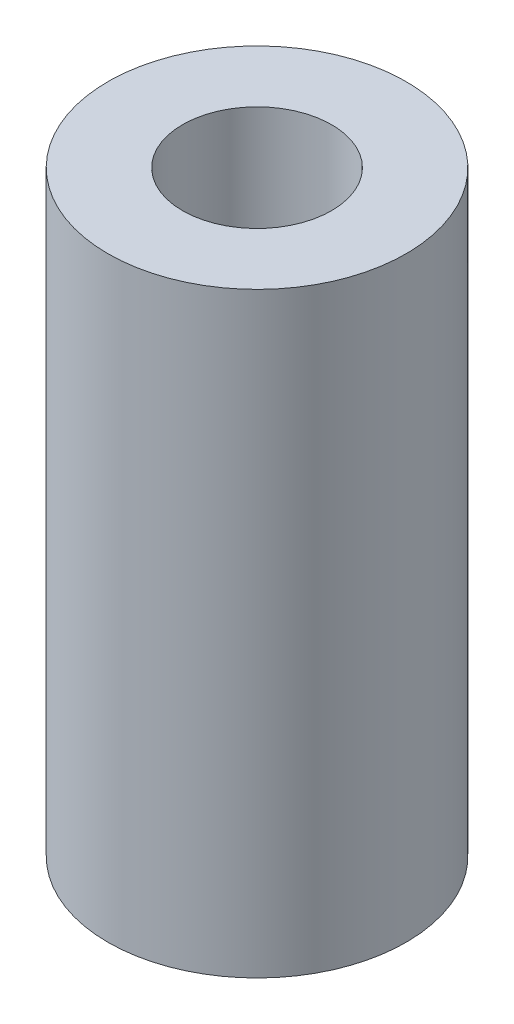
SolidWorks part; units mm, degrees
material "6061-T6 (SS)"
ref_plane "Front Plane" through (0, 0, 0) normal (0, 0, 1) x (1, 0, 0)
ref_plane "Top Plane" through (0, 0, 0) normal (0, 1, 0) x (1, 0, 0)
ref_plane "Right Plane" through (0, 0, 0) normal (1, 0, 0) x (0, 0, -1)
sketch "Sketch1" plane through (0, 0, 0) normal (0, 1, 0) x (1, 0, 0)
  circle A0 centre (0, 0) radius 6.35
  circle A1 centre (0, 0) radius 3.175
  dimension "D1" = 12.7
  dimension "D2" = 6.35
extrude "Boss-Extrude1" add sketch "Sketch1" along normal blind 25.4
